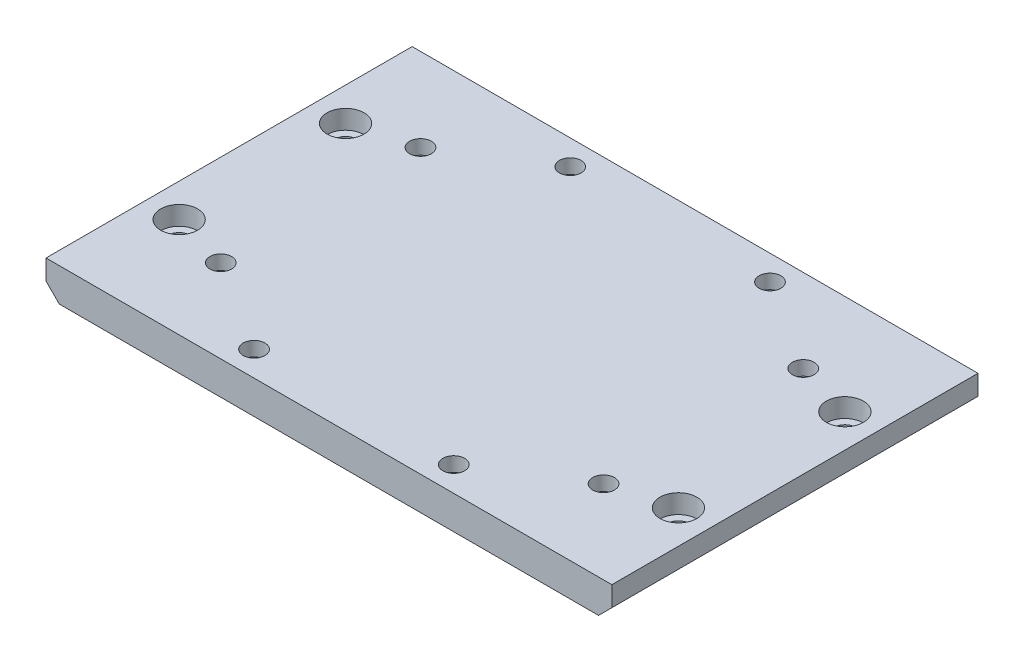
SolidWorks part; units mm, degrees
material "6061 Alloy"
ref_plane "Front Plane" through (0, 0, 0) normal (0, 0, 1) x (1, 0, 0)
ref_plane "Top Plane" through (0, 0, 0) normal (0, 1, 0) x (1, 0, 0)
ref_plane "Right Plane" through (0, 0, 0) normal (1, 0, 0) x (0, 0, -1)
sketch "Sketch2" plane through (0, 0, 0) normal (0, 1, 0) x (1, 0, 0)
  line L1 (27.5, -27.5) -> (-27.5, -27.5)
  line L2 (27.5, -27.5) -> (27.5, 27.5)
  line L3 (27.5, 27.5) -> (-27.5, 27.5)
  line L4 (-27.5, -27.5) -> (-27.5, 27.5)
  line L5 (27.5, -27.5) -> (-27.5, 27.5) construction
  line L6 (27.5, 27.5) -> (-27.5, -27.5) construction
  point P0 (0, 0)
  dimension "D1" = 55
  dimension "D2" = 55
extrude "Boss-Extrude1" add sketch "Sketch2" along normal blind 5
sketch "Sketch3" plane through (0, 0, 0) normal (0, -1, 0) x (1, 0, 0)
  line L1 (28.75, -23.75) -> (-28.75, -23.75)
  line L2 (28.75, -23.75) -> (28.75, 23.75)
  line L3 (28.75, 23.75) -> (-28.75, 23.75)
  line L4 (-28.75, -23.75) -> (-28.75, 23.75)
  line L5 (28.75, -23.75) -> (-28.75, 23.75) construction
  line L6 (28.75, 23.75) -> (-28.75, -23.75) construction
  line L7 (15, -23.75) -> (-15, -23.75)
  line L8 (15, -23.75) -> (15, 23.75)
  line L9 (15, 23.75) -> (-15, 23.75)
  line L10 (-15, -23.75) -> (-15, 23.75)
  line L11 (15, -23.75) -> (-15, 23.75) construction
  line L12 (15, 23.75) -> (-15, -23.75) construction
  line L13 (28.75, -15) -> (-28.75, -15)
  line L14 (28.75, -15) -> (28.75, 15)
  line L15 (28.75, 15) -> (-28.75, 15)
  line L16 (-28.75, -15) -> (-28.75, 15)
  line L17 (28.75, -15) -> (-28.75, 15) construction
  line L18 (28.75, 15) -> (-28.75, -15) construction
  point P0 (0, 0)
  point P5 (0, 0)
  point P11 (0, 0)
  dimension "D1" = 57.5
  dimension "D2" = 47.5
  dimension "D3" = 30
  dimension "D4" = 30
sketch "Sketch6" plane through (0, 0, 0) normal (0, -1, 0) x (1, 0, 0)
  line L1 (-27.5, 27.5) -> (-42.5, 27.5)
  line L2 (-27.5, 27.5) -> (-27.5, -27.5)
  line L3 (-27.5, -27.5) -> (-42.5, -27.5)
  line L4 (-42.5, 27.5) -> (-42.5, -27.5)
  line L5 (27.5, 27.5) -> (42.5, 27.5)
  line L6 (27.5, 27.5) -> (27.5, -27.5)
  line L7 (27.5, -27.5) -> (42.5, -27.5)
  line L8 (42.5, 27.5) -> (42.5, -27.5)
  dimension "D1" = 85
  dimension "D2" = 15
  dimension "D3" = 55
  dimension "D4" = 55
extrude "Boss-Extrude2" add sketch "Sketch6" against normal up to surface (5 mm away) up to face at (0, 5, 0)
sketch "Sketch7" plane through (0, 5, 0) normal (0, 1, 0) x (1, 0, 0)
  line L1 (37.5, -12.5) -> (-37.5, -12.5)
  line L2 (37.5, -12.5) -> (37.5, 12.5)
  line L3 (37.5, 12.5) -> (-37.5, 12.5)
  line L4 (-37.5, -12.5) -> (-37.5, 12.5)
  line L5 (37.5, -12.5) -> (-37.5, 12.5) construction
  line L6 (37.5, 12.5) -> (-37.5, -12.5) construction
  point P0 (0, 0)
  dimension "D1" = 75
  dimension "D2" = 25
hole_wizard "CBORE for #4 Socket Head Cap Screw2" positions "Sketch8" profile "Sketch9" counterbore size "#4" standard "ANSI Inch" end condition up to next
sketch "Sketch8" plane through (0, 5, 0) normal (0, 1, 0) x (1, 0, 0)
  point P0 (-37.5, 12.5)
  point P3 (-37.5, -12.5)
  point P6 (37.5, -12.5)
  point P9 (37.5, 12.5)
sketch "Sketch9" plane through (-37.5, 5, -12.5) normal (1, 0, 0) x (0, 0, 1)
  line L0 (0, 0) -> (0, 5)
  line L1 (0, 5) -> (1.6319, 5)
  line L3 (1.6319, 5) -> (1.632, 2.8448)
  line L4 (1.632, 2.8448) -> (2.7788, 2.8448)
  line L5 (2.7788, 2.8448) -> (2.7788, 0)
  line L7 (2.7788, 0) -> (0, 0)
  line L11 (0, -6.35) -> (0, 107.95) construction
  dimension "Thru Hole Dia." = 3.2639
  dimension "Thru Hole Depth" = 5
  dimension "C'Bore Dia." = 5.5575
  dimension "C'Bore Depth" = 2.8448
hole_wizard "CBORE for #4 Socket Head Cap Screw3" positions "Sketch12" profile "Sketch13" counterbore size "#4" standard "ANSI Inch" end condition through all
sketch "Sketch12" plane through (0, 0, 0) normal (0, -1, 0) x (-1, 0, 0)
  point P0 (-28.75, 15)
  point P3 (-15, 23.75)
  point P6 (-28.75, -15)
  point P9 (-15, -23.75)
  point P12 (15, -23.75)
  point P15 (28.75, -15)
  point P18 (28.75, 15)
  point P22 (15, 23.75)
sketch "Sketch13" plane through (28.75, 0, -15) normal (1, 0, 0) x (0, 0, -1)
  line L0 (0, 0) -> (0, 5)
  line L1 (0, 5) -> (1.6319, 5)
  line L3 (1.6319, 5) -> (1.6319, 2.8448)
  line L4 (1.6319, 2.8448) -> (2.7788, 2.8448)
  line L5 (2.7788, 2.8448) -> (2.7788, 0)
  line L7 (2.7788, 0) -> (0, 0)
  line L11 (0, -6.35) -> (0, 107.95) construction
  dimension "Thru Hole Dia." = 3.2639
  dimension "Thru Hole Depth" = 5
  dimension "C'Bore Dia." = 5.5575
  dimension "C'Bore Depth" = 2.8448
chamfer "Chamfer1" distance 2 angle 45 2 edges at (-42.5, 0, 0) (42.5, 0, 0)
